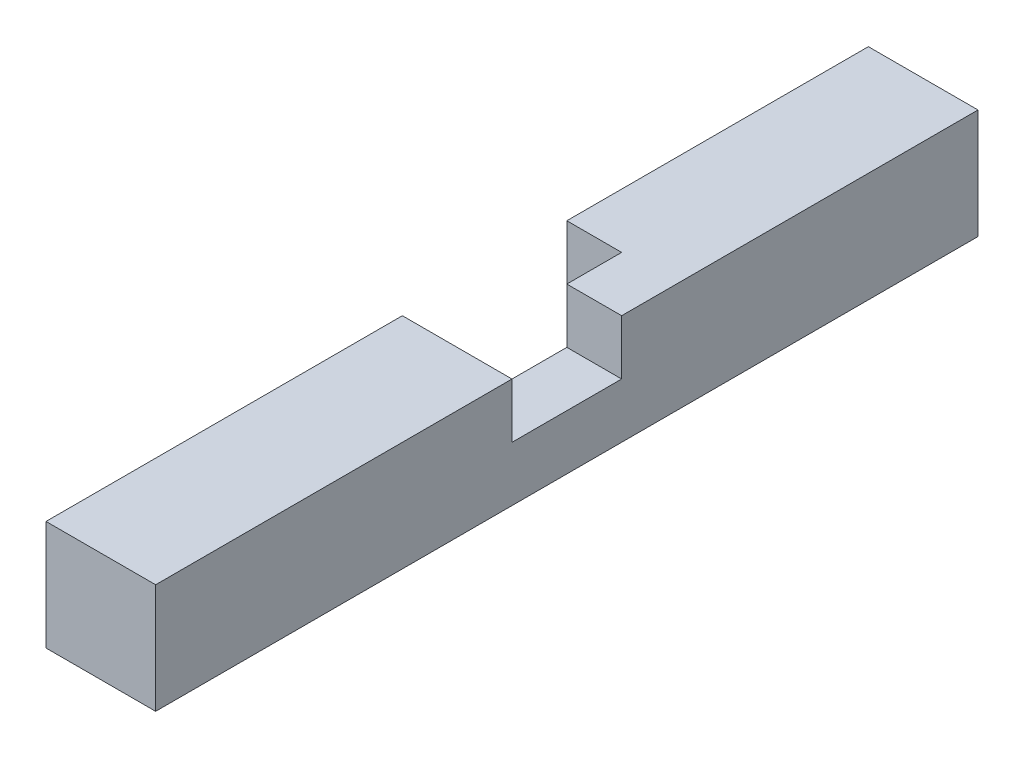
SolidWorks part; units mm, degrees
ref_plane "前基準面" through (0, 0, 0) normal (0, 0, 1) x (1, 0, 0)
ref_plane "上基準面" through (0, 0, 0) normal (0, 1, 0) x (1, 0, 0)
ref_plane "右基準面" through (0, 0, 0) normal (1, 0, 0) x (0, 0, -1)
sketch "草圖1" plane through (0, 0, 0) normal (0, 0, 1) x (1, 0, 0)
  line L1 (-2, 2) -> (2, 2)
  line L2 (-2, 2) -> (-2, -2)
  line L3 (-2, -2) -> (2, -2)
  line L4 (2, 2) -> (2, -2)
  line L5 (-2, 2) -> (2, -2) construction
  line L6 (-2, -2) -> (2, 2) construction
  point P0 (0, 0)
extrude "填料-伸長1" add sketch "草圖1" along normal blind 30
sketch "草圖2" plane through (-2, 0, 0) normal (-1, 0, 0) x (0, 0, 1)
  line L0 (30, -2) -> (0, -2) construction
  line L1 (0, 2) -> (11, 2)
  line L2 (0, 2) -> (0, -2)
  line L3 (0, -2) -> (11, -2)
  line L4 (11, 2) -> (11, -2)
sketch "草圖3" plane through (-2, 0, 0) normal (-1, 0, 0) x (0, 0, 1)
  line L0 (30, -2) -> (0, -2) construction
  line L1 (11, 2) -> (13, 2)
  line L2 (11, 2) -> (11, -2)
  line L3 (11, -2) -> (13, -2)
  line L4 (13, 2) -> (13, -2)
extrude "除料-伸長1" cut sketch "草圖3" against normal blind 2
sketch "草圖4" plane through (-2, 0, 0) normal (-1, 0, 0) x (0, 0, 1)
  line L1 (13, 2) -> (17, 2)
  line L2 (13, 2) -> (13, 0)
  line L3 (13, 0) -> (17, 0)
  line L4 (17, 2) -> (17, 0)
extrude "除料-伸長2" cut sketch "草圖4" against normal blind 4 contours L3 L4 L1 L2
sketch "草圖5" plane through (-2, 0, 0) normal (-1, 0, 0) x (0, 0, 1)
  line L0 (30, -2) -> (13, -2) construction
  line L1 (13, 0) -> (15, 0)
  line L2 (13, 0) -> (13, -2)
  line L3 (13, -2) -> (15, -2)
  line L4 (15, 0) -> (15, -2)
extrude "除料-伸長3" cut sketch "草圖5" against normal blind 2 contours L4 L3 L2 L1
